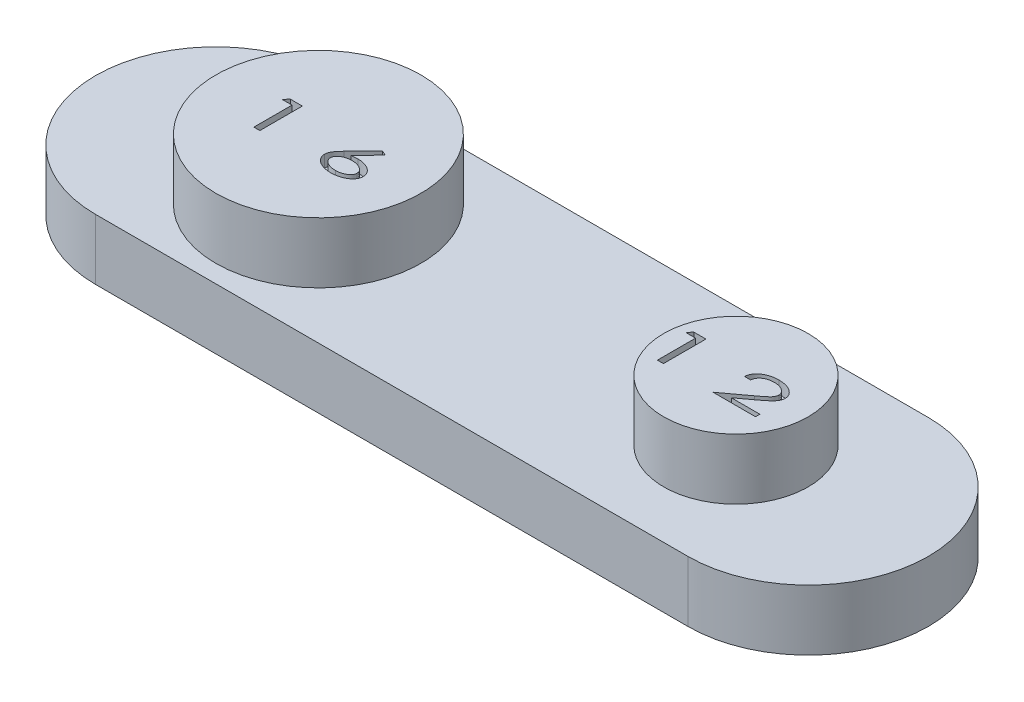
SolidWorks part; units mm, degrees
ref_plane "Спереди" through (0, 0, 0) normal (0, 0, 1) x (1, 0, 0)
ref_plane "Сверху" through (0, 0, 0) normal (0, 1, 0) x (1, 0, 0)
ref_plane "Справа" through (0, 0, 0) normal (1, 0, 0) x (0, 0, -1)
sketch "Эскиз1" plane through (0, 0, 0) normal (0, 1, 0) x (1, 0, 0)
  line L0 (0, 0) -> (20, 0) construction
  line L1 (36.9, 0) -> (56.9, 0) construction
  line L2 (68.8, 0) -> (88.8, 0) construction
  line L3 (28.45, 8.45) -> (28.45, 28.45) construction
  line L4 (28.45, -8.45) -> (28.45, -28.45) construction
  circle A0 centre (28.45, 0) radius 8.45
  circle A1 centre (62.85, 0) radius 5.95
  dimension "D1" = 16.9
  dimension "D2" = 11.9
  dimension "D3" = 20
extrude "Бобышка-Вытянуть1" add sketch "Эскиз1" along normal blind 5
sketch "Эскиз2" plane through (0, 0, 0) normal (0, -1, 0) x (1, 0, 0)
  line L0 (20, 0) -> (68.8, 0) construction
  line L1 (20, 0) -> (68.8, 0) construction
  line L2 (20, 9.9071) -> (68.8, 9.9071)
  line L3 (20, -9.9071) -> (68.8, -9.9071)
  circle A0 centre (28.45, 0) radius 8.45 construction
  circle A1 centre (62.85, 0) radius 5.95 construction
  arc A2 (20, 9.9071) -> (20, -9.9071) centre (20, 0) ccw
  arc A3 (68.8, -9.9071) -> (68.8, 9.9071) centre (68.8, 0) ccw
  point P8 (44.4, 0)
extrude "Бобышка-Вытянуть2" add sketch "Эскиз2" along normal blind 5
sketch "Эскиз3" plane through (0, 5, 0) normal (0, 1, 0) x (1, 0, 0)
  text T0 "16     12" font "Century Gothic" height 3.5
extrude "Вырез-Вытянуть1" cut sketch "Эскиз3" against normal blind 1
